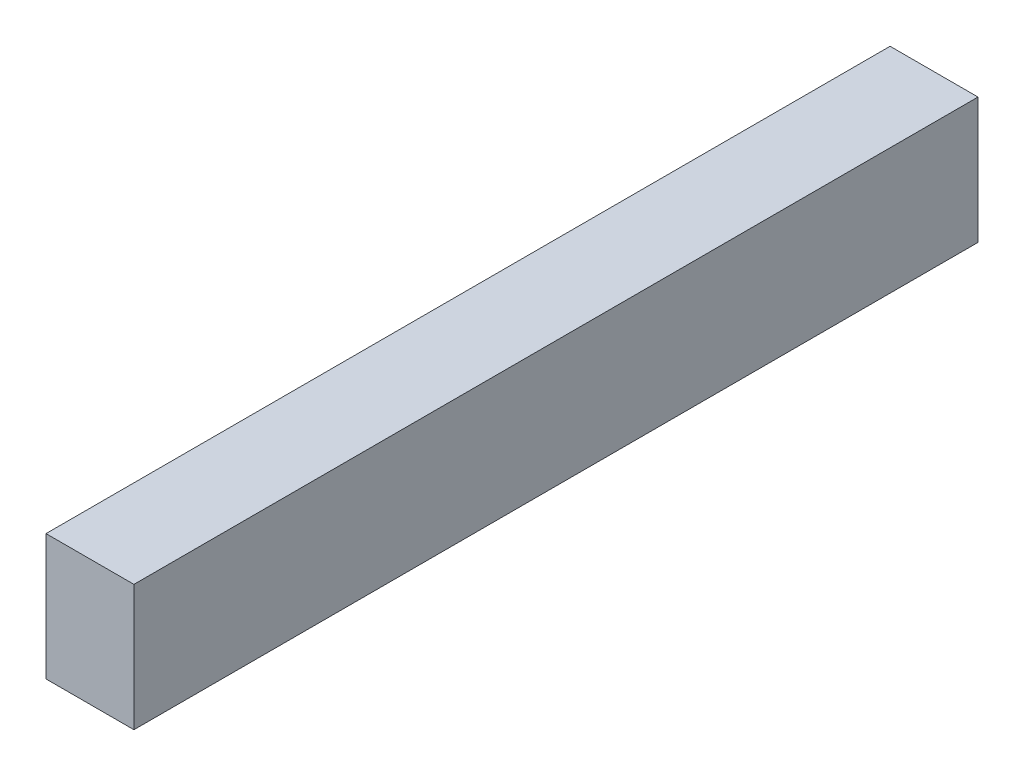
SolidWorks part; units mm, degrees
material "Brass"
ref_plane "Front Plane" through (0, 0, 0) normal (0, 0, 1) x (1, 0, 0)
ref_plane "Top Plane" through (0, 0, 0) normal (0, 1, 0) x (1, 0, 0)
ref_plane "Right Plane" through (0, 0, 0) normal (1, 0, 0) x (0, 0, -1)
sketch "Sketch1" plane through (0, 0, 0) normal (0, 0, 1) x (1, 0, 0)
  line L1 (1.5875, -2.2733) -> (-1.5875, -2.2733)
  line L2 (1.5875, -2.2733) -> (1.5875, 2.2733)
  line L3 (1.5875, 2.2733) -> (-1.5875, 2.2733)
  line L4 (-1.5875, -2.2733) -> (-1.5875, 2.2733)
  line L5 (1.5875, -2.2733) -> (-1.5875, 2.2733) construction
  line L6 (1.5875, 2.2733) -> (-1.5875, -2.2733) construction
  point P0 (0, 0)
  dimension "D1" = 4.5466
  dimension "D2" = 3.175
extrude "Boss-Extrude1" add sketch "Sketch1" along normal mid plane 30.48
